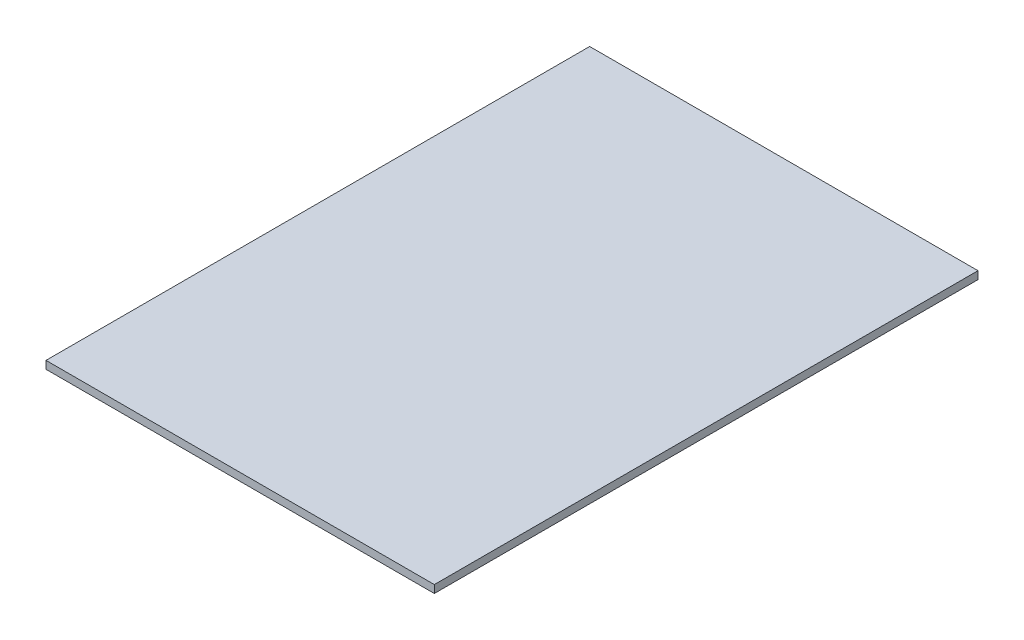
SolidWorks part; units mm, degrees
ref_plane "Plan de face" through (0, 0, 0) normal (0, 0, 1) x (1, 0, 0)
ref_plane "Plan de dessus" through (0, 0, 0) normal (0, 1, 0) x (1, 0, 0)
ref_plane "Plan de droite" through (0, 0, 0) normal (1, 0, 0) x (0, 0, -1)
sketch "Esquisse1" plane through (0, 0, 0) normal (0, 1, 0) x (1, 0, 0)
  line L1 (0, 0) -> (250, 0)
  line L2 (0, 0) -> (0, 350)
  line L3 (0, 350) -> (250, 350)
  line L4 (250, 0) -> (250, 350)
  point P9 (0, 0)
extrude "Boss.-Extru.1" add sketch "Esquisse1" along normal blind 5
